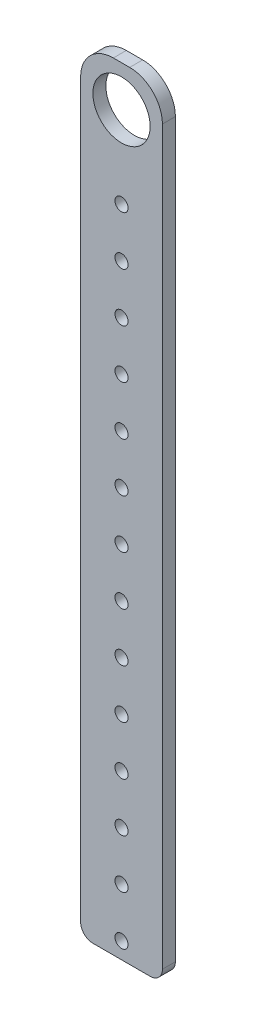
SolidWorks part; units mm, degrees
ref_plane "Front Plane" through (0, 0, 0) normal (0, 0, 1) x (1, 0, 0)
ref_plane "Top Plane" through (0, 0, 0) normal (0, 1, 0) x (1, 0, 0)
ref_plane "Right Plane" through (0, 0, 0) normal (1, 0, 0) x (0, 0, -1)
sketch "Sketch1" plane through (0, 0, 0) normal (0, 0, 1) x (1, 0, 0)
  line L0 (0, 95) -> (0, -95) construction
  line L1 (-10, -95) -> (10, -95)
  line L2 (-10, -95) -> (-10, 95)
  line L3 (-10, 95) -> (10, 95)
  line L4 (10, -95) -> (10, 95)
  line L5 (-10, -95) -> (10, 95) construction
  line L6 (-10, 95) -> (10, -95) construction
  circle A26 centre (0, -91) radius 1.6
  circle A27 centre (0, -79) radius 1.6
  circle A28 centre (0, -67) radius 1.6
  circle A29 centre (0, -55) radius 1.6
  circle A30 centre (0, -43) radius 1.6
  circle A31 centre (0, -31) radius 1.6
  circle A32 centre (0, -19) radius 1.6
  circle A33 centre (0, 85) radius 7
  circle A34 centre (0, -7) radius 1.6
  circle A35 centre (0, 5) radius 1.6
  circle A36 centre (0, 17) radius 1.6
  circle A37 centre (0, 29) radius 1.6
  circle A38 centre (0, 41) radius 1.6
  circle A39 centre (0, 53) radius 1.6
  circle A40 centre (0, 65) radius 1.6
  point P0 (0, 0)
  dimension "D3" = 14
  dimension "D8" = 3.2
  dimension "D1" = 190
  dimension "D2" = 20
  dimension "D4" = 10
  dimension "D9" = 4
  dimension "D10" = 14
extrude "Boss-Extrude1" add sketch "Sketch1" along normal blind 3.175
fillet "Fillet1" radius 3 2 edges at (10, -95, 1.5875) (-10, -95, 1.5875)
fillet "Fillet2" radius 8 2 edges at (10, 95, 1.5875) (-10, 95, 1.5875)
